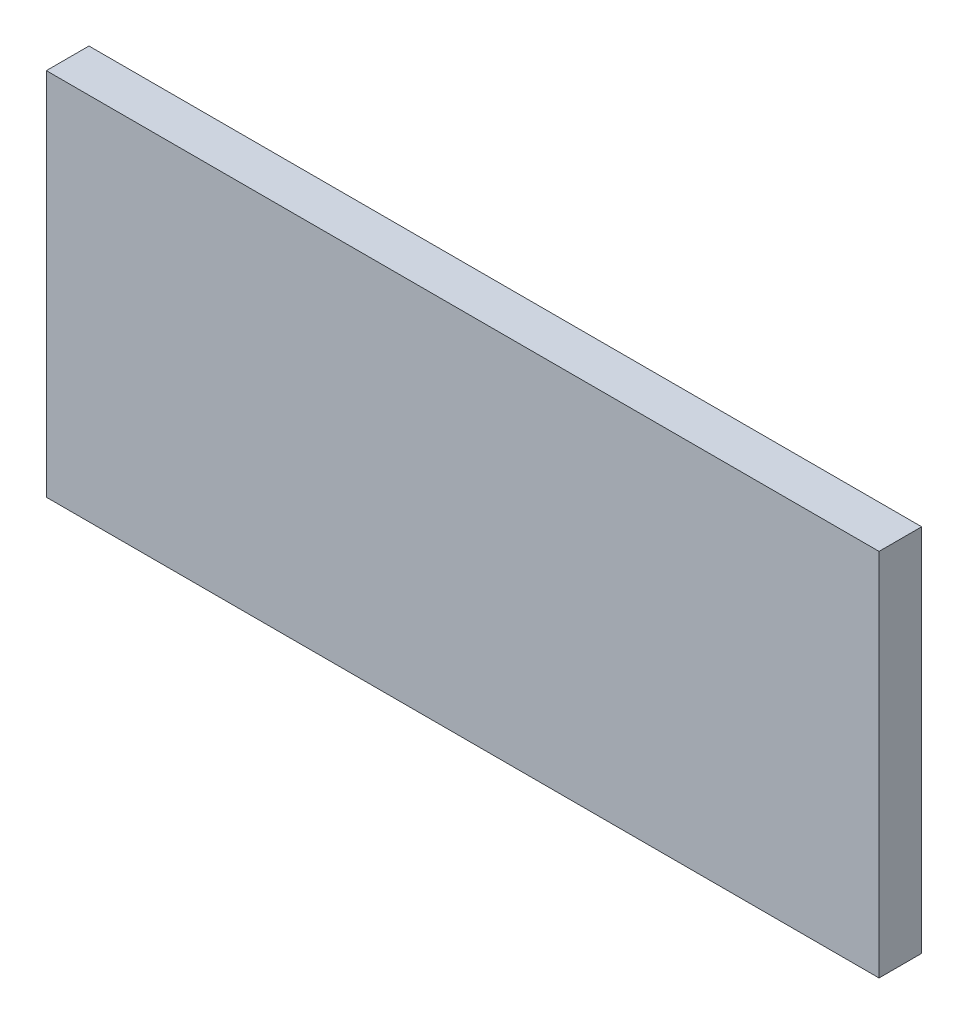
SolidWorks part; units mm, degrees
material "Klon"
ref_plane "Płaszczyzna przednia" through (0, 0, 0) normal (0, 0, 1) x (1, 0, 0)
ref_plane "Płaszczyzna górna" through (0, 0, 0) normal (0, 1, 0) x (1, 0, 0)
ref_plane "Płaszczyzna prawa" through (0, 0, 0) normal (1, 0, 0) x (0, 0, -1)
sketch "Szkic1" plane through (0, 0, 0) normal (0, 1, 0) x (1, 0, 0)
  line L1 (-146.5, -7.5) -> (146.5, -7.5)
  line L2 (-146.5, -7.5) -> (-146.5, 7.5)
  line L3 (-146.5, 7.5) -> (146.5, 7.5)
  line L4 (146.5, -7.5) -> (146.5, 7.5)
  line L5 (-146.5, -7.5) -> (146.5, 7.5) construction
  line L6 (-146.5, 7.5) -> (146.5, -7.5) construction
  point P0 (0, 0)
  dimension "D1" = 15
  dimension "D2" = 293
extrude "Dodanie-wyciągnięcie1" add sketch "Szkic1" along normal blind 130
